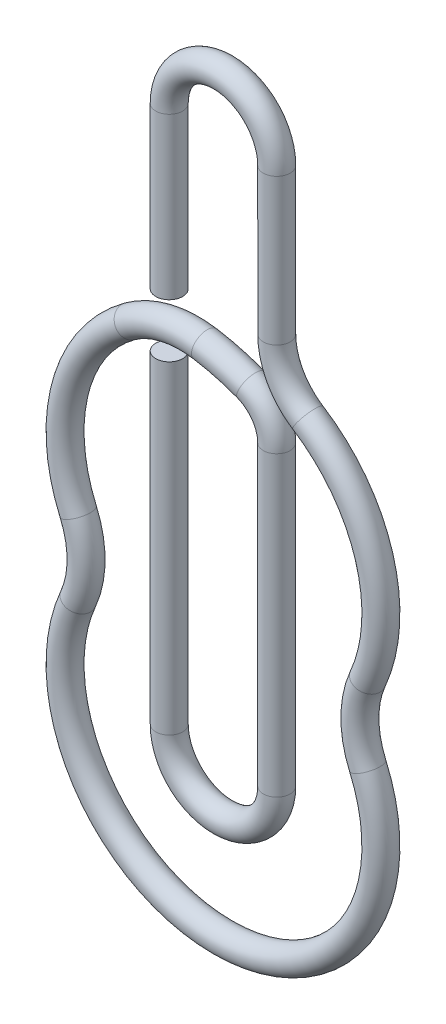
SolidWorks part; units mm, degrees
ref_plane "Спереди" through (0, 0, 0) normal (0, 0, 1) x (1, 0, 0)
ref_plane "Сверху" through (0, 0, 0) normal (0, 1, 0) x (1, 0, 0)
ref_plane "Справа" through (0, 0, 0) normal (1, 0, 0) x (0, 0, -1)
sketch "Эскиз1" plane through (0, 0, 0) normal (0, 0, 1) x (1, 0, 0)
  line L0 (0, 0) -> (10.7157, 0) construction
  line L1 (0, 65) -> (0, -15) construction
  line L2 (8, 65) -> (8, -15) construction
  line L3 (-8, 65) -> (-8, -15) construction
  circle A0 centre (0, 15) radius 23.5 construction
  circle A1 centre (0, -15) radius 23.5 construction
  arc A2 (8, 65) -> (-8, 65) centre (0, 65) ccw construction
  arc A3 (-8, -15) -> (8, -15) centre (0, -15) ccw construction
  arc A4 (-8, 37.0964) -> (8, 33.0964) centre (-8, 3.0964) cw construction
  point P9 (0, 25)
  point P17 (8, 37.0964)
  dimension "D2" = 47
  dimension "D1" = 15
  dimension "D3" = 80
  dimension "D4" = 16
  dimension "D5" = 25
  dimension "D6" = 4
ref_plane "Плоскость1" through (0, 0, 4) normal (0, 0, 1) x (1, 0, 0)
sketch "Эскиз3" plane through (0, 0, 0) normal (0, 0, 1) x (1, 0, 0)
  line L0 (8, 29.2498) -> (8, -15)
  line L1 (-8, -15) -> (-8, 33.0964)
  line L2 (-8, 65) -> (-8, -15) construction
  line L3 (8, 43.2533) -> (8, 65)
  line L4 (-8, 65) -> (-8, 41.0964)
  arc A0 (-21.5381, -5.6) -> (21.5381, -5.6) centre (0, -15) ccw
  circle A1 centre (0, 15) radius 23.5 construction
  circle A2 centre (0, -15) radius 23.5 construction
  arc A3 (-21.5381, 5.6) -> (-13.8727, 33.9683) centre (0, 15) cw
  arc A4 (8, 33.0964) -> (-8, 37.0964) centre (-8, 3.0964) ccw construction
  arc A5 (12.6269, 34.8195) -> (21.5381, 5.6) centre (0, 15) cw
  arc A6 (8, -15) -> (-8, -15) centre (0, -15) cw
  arc A7 (8, 65) -> (-8, 65) centre (0, 65) ccw
  arc A8 (4.1429, 34.8541) -> (-2.6634, 36.675) centre (-8, 3.0964) ccw
  arc A9 (8, 29.2498) -> (4.1429, 34.8541) centre (2, 29.2498) ccw
  arc A10 (-21.5381, 5.6) -> (-21.5381, -5.6) centre (-34.3693, 0) cw
  arc A11 (21.5381, 5.6) -> (21.5381, -5.6) centre (34.3693, 0) ccw
  arc A12 (8, 43.2533) -> (12.6269, 34.8195) centre (18, 43.2533) ccw
  arc A13 (-2.6634, 36.675) -> (-13.8727, 33.9683) centre (-5.0178, 21.8609) ccw
  point P35 (-18.0901, 0)
  point P38 (18.0901, 0)
  point P41 (8, 37.0964)
  dimension "D3" = 6
  dimension "D4" = 14
  dimension "D5" = 10
  dimension "D6" = 15
  dimension "D1" = 4
  dimension "D2" = 4
ref_plane "Плоскость2" through (-8, 41.0964, 0) normal (0, -1, 0) x (-1, 0, 0)
sketch "Эскиз4" plane through (-8, 41.0964, 0) normal (0, -1, 0) x (-1, 0, 0)
  circle A0 centre (0, 0) radius 2
  dimension "D1" = 4
sweep "По траектории2" add profiles "Эскиз4" path "Эскиз3"
